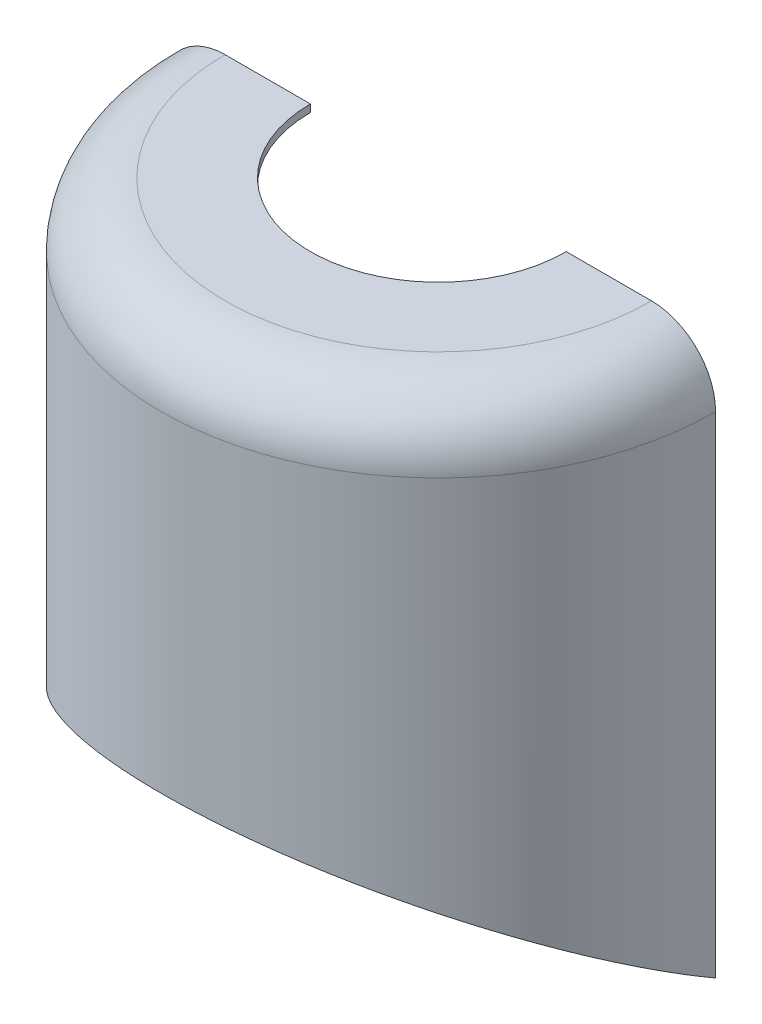
SolidWorks part; units mm, degrees
ref_plane "Front Plane" through (0, 0, 0) normal (0, 0, 1) x (1, 0, 0)
ref_plane "Top Plane" through (0, 0, 0) normal (0, 1, 0) x (1, 0, 0)
ref_plane "Right Plane" through (0, 0, 0) normal (1, 0, 0) x (0, 0, -1)
sketch "Sketch1" plane through (0, 0, 0) normal (0, 1, 0) x (1, 0, 0)
  line L3 (26, 13) -> (-26, 13)
  line L5 (15.6, -7.8) -> (-26, 13) construction
  line L6 (26, 13) -> (-15.6, -7.8) construction
  arc A0 (-26, 13) -> (26, 13) centre (0, 13) ccw
  point P0 (0, 0)
  dimension "D2" = 52
extrude "Boss-Extrude1" add sketch "Sketch1" along normal blind 52
fillet "Fillet1" radius 6 1 edges at (0, 52, 13)
sketch "Sketch2" plane through (0, 0, 0) normal (1, 0, 0) x (0, 0, -1)
  line L0 (13, 0) -> (-13, 15)
  line L1 (-13, 46) -> (-13, 0) construction
  line L2 (-13, 15) -> (-13, 0)
  line L3 (-13, 0) -> (13, 0)
  line L4 (13, 52) -> (-7, 52) construction
  dimension "D1" = 37
extrude "Cut-Extrude1" cut sketch "Sketch2" against normal through all both and the other way through all
shell "Shell1" thickness 0.7
sketch "Sketch3" plane through (0, 52, 0) normal (0, 1, 0) x (1, 0, 0)
  line L0 (20, 13) -> (-20, 13) construction
  circle A0 centre (0, 13) radius 12
  dimension "D1" = 24
extrude "Cut-Extrude2" cut sketch "Sketch3" against normal blind 32
